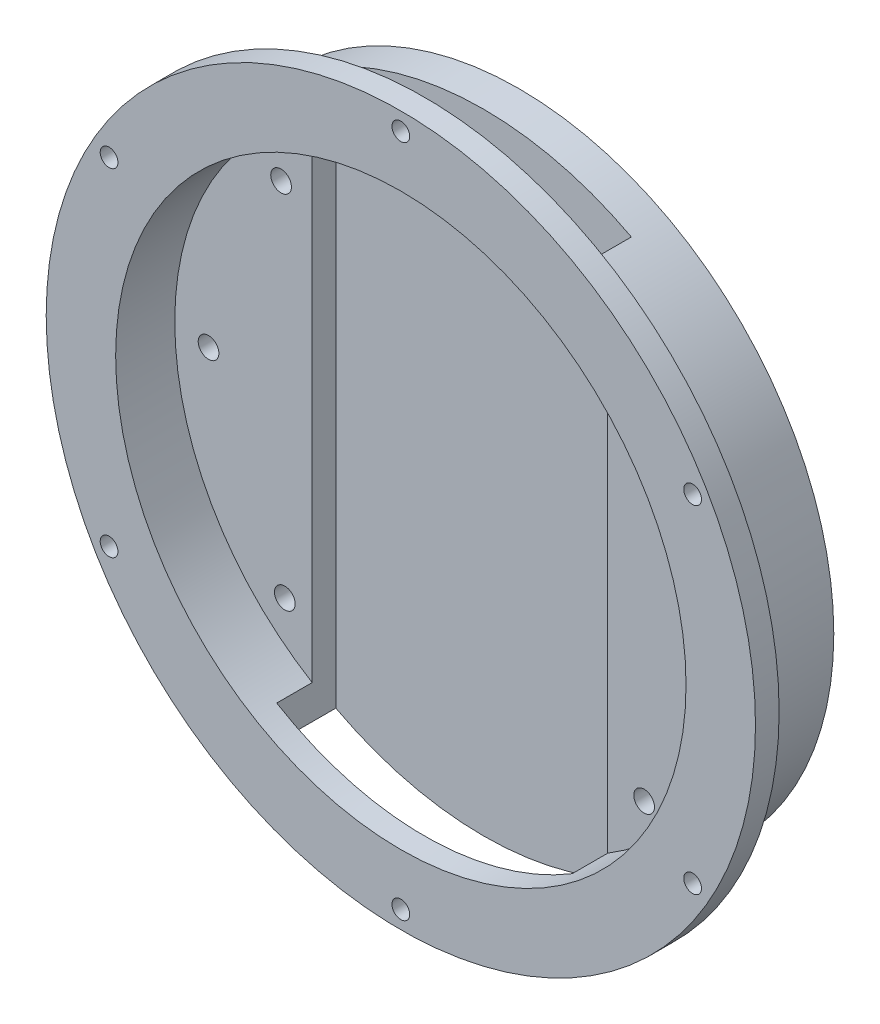
SolidWorks part; units mm, degrees
ref_plane "前视基准面" through (0, 0, 0) normal (0, 0, 1) x (1, 0, 0)
ref_plane "上视基准面" through (0, 0, 0) normal (0, 1, 0) x (1, 0, 0)
ref_plane "右视基准面" through (0, 0, 0) normal (1, 0, 0) x (0, 0, -1)
sketch "草图1" plane through (0, 0, 0) normal (0, 0, 1) x (1, 0, 0)
  arc A0 (-28.0418, -31.936) -> (-0.5596, -42.4963) centre (0, 0) ccw
  circle A1 centre (0, 0) radius 48.25
  circle A3 centre (0, 42.5) radius 1.75
  circle A4 centre (30.5245, 30.2285) radius 1.75
  circle A5 centre (43.4313, -0.0329) radius 1.75
  circle A6 centre (31.1598, -30.5574) radius 1.75
  circle A7 centre (0.8984, -43.4642) radius 1.75
  circle A8 centre (-29.6261, -31.1927) radius 1.75
  circle A9 centre (-42.5329, -0.9313) radius 1.75
  circle A10 centre (-30.2614, 29.5932) radius 1.75
  arc A11 (2.3152, -42.4369) -> (29.4139, -30.6769) centre (0, 0) ccw
  arc A12 (31.2452, -28.8095) -> (42.4736, -1.4976) centre (0, 0) ccw
  arc A13 (42.4758, 1.4333) -> (31.3561, 28.6887) centre (0, 0) ccw
  arc A14 (28.9929, 31.0751) -> (1.7496, 42.464) centre (0, 0) ccw
  arc A15 (-1.7496, 42.464) -> (-29.1403, 30.9369) centre (0, 0) ccw
  arc A16 (-31.5797, 28.4424) -> (-42.4921, 0.8182) centre (0, 0) ccw
  arc A17 (-42.4156, -2.6774) -> (-30.45, -29.6487) centre (0, 0) ccw
  point P23 (0.4492, -0.4821)
  dimension "D1" = 85
  dimension "D2" = 96.5
  dimension "D3" = 3.5
  dimension "D4" = 8
extrude "凸台-拉伸1" add sketch "草图1" along normal blind 15 contours A5 | A6 | A7 | A8 | A9 | A10 | A3 | A4
sketch "草图2" plane through (0, 0, 0) normal (0, 0, 1) x (1, 0, 0)
  circle A0 centre (0, 0) radius 48.25 construction
  circle A1 centre (0, 0) radius 48.25
extrude "凸台-拉伸2" add sketch "草图2" against normal blind 5
sketch "草图3" plane through (0, 0, -5) normal (0, 0, -1) x (-1, 0, 0)
  circle A0 centre (0, 0) radius 48.25 construction
  circle A1 centre (0, 0) radius 48.25
extrude "拉伸-薄壁1" add sketch "草图3" against normal blind 15 thin
sketch "草图4" plane through (0, 0, 10) normal (0, 0, 1) x (1, 0, 0)
  circle A0 centre (0, 0) radius 60
  circle A1 centre (0, 0) radius 48.25 construction
  circle A4 centre (0, 0) radius 48.25
  dimension "D2" = 120
extrude "凸台-拉伸3" add sketch "草图4" against normal blind 4
sketch "草图5" plane through (0, 0, 6) normal (0, 0, -1) x (-1, 0, 0)
  line L0 (0, 0) -> (0, 74.6783) construction
  circle A0 centre (0, 0) radius 53.25 construction
  circle A1 centre (0, 0) radius 57
  circle A5 centre (0, 56.625) radius 1.5
  circle A6 centre (49.3634, 28.5) radius 1.5
  circle A7 centre (49.6882, -28.3125) radius 1.5
  circle A8 centre (0.6495, -57) radius 1.5
  circle A9 centre (-48.7139, -28.875) radius 1.5
  circle A10 centre (-49.0387, 27.9375) radius 1.5
  point P22 (0.3248, -0.1875)
  dimension "D3" = 3
  dimension "D1" = 114
  dimension "D4" = 6
sketch "草图6" plane through (0, 0, 6) normal (0, 0, -1) x (-1, 0, 0)
  circle A3 centre (0, 57) radius 1.5
  circle A4 centre (49.3634, 28.5) radius 1.5
  circle A5 centre (49.3634, -28.5) radius 1.5
  circle A6 centre (0, -57) radius 1.5
  circle A7 centre (-49.3634, -28.5) radius 1.5
  circle A8 centre (-49.3634, 28.5) radius 1.5
  point P19 (0, 0)
  dimension "D3" = 3
  dimension "D4" = 6
extrude "切除-拉伸1" cut sketch "草图6" against normal up to next
sketch "草图7" plane through (0, 0, -5) normal (0, 0, -1) x (-1, 0, 0)
  circle A0 centre (49.3634, -28.5) radius 1.5 construction
  circle A1 centre (49.3634, -28.5) radius 1.5
  circle A2 centre (0, 0) radius 53.25 construction
  circle A3 centre (0, 0) radius 53.25
  dimension "D1" = 57
sketch "草图8" plane through (0, 0, 15) normal (0, 0, 1) x (1, 0, 0)
  circle A0 centre (-49.3634, 28.5) radius 1.5 construction
  circle A1 centre (-42.5329, -0.9313) radius 1.75
  circle A2 centre (-42.5329, -0.9313) radius 1.75
  circle A3 centre (-49.3634, 28.5) radius 1.5
  point P8 (0, 0)
  dimension "D1" = 0
ref_plane "基准面1" through (0, 10, 0) normal (0, 1, 0) x (1, 0, 0)
sketch "草图9" plane through (0, 10, 0) normal (0, 1, 0) x (1, 0, 0)
  line L1 (-25, 4) -> (25, 4)
  line L2 (60, -6) -> (-60, -6) construction
  line L3 (25, -6) -> (-25, -6)
  line L4 (25, 4) -> (25, -6)
  line L5 (-25, 4) -> (-25, -6)
  point P0 (0, 4)
  dimension "D1" = 25
  dimension "D2" = 25
  dimension "D3" = 10
extrude "切除-拉伸3" cut sketch "草图9" against normal through all and the other way through all
sketch "草图10" plane through (0, 0, -5) normal (0, 0, -1) x (-1, 0, 0)
  circle A1 centre (0, 0) radius 53.25
  circle A2 centre (0, 0) radius 53.25
  dimension "D1" = 0
extrude "凸台-拉伸4" add sketch "草图10" along normal blind 5
sketch "草图11" plane through (0, 0, -10) normal (0, 0, -1) x (-1, 0, 0)
  circle A0 centre (30.2614, 29.5932) radius 1.75 construction
  circle A1 centre (42.5329, -0.9313) radius 1.75 construction
  circle A2 centre (29.6261, -31.1927) radius 1.75 construction
  circle A3 centre (-31.1598, -30.5574) radius 1.75 construction
  circle A4 centre (-43.4313, -0.0329) radius 1.75 construction
  circle A5 centre (-30.5245, 30.2285) radius 1.75 construction
  circle A6 centre (30.2614, 29.5932) radius 1.75
  circle A7 centre (42.5329, -0.9313) radius 1.75
  circle A8 centre (29.6261, -31.1927) radius 1.75
  circle A9 centre (-31.1598, -30.5574) radius 1.75
  circle A10 centre (-43.4313, -0.0329) radius 1.75
  circle A11 centre (-30.5245, 30.2285) radius 1.75
extrude "切除-拉伸4" cut sketch "草图11" against normal through all and the other way through all
